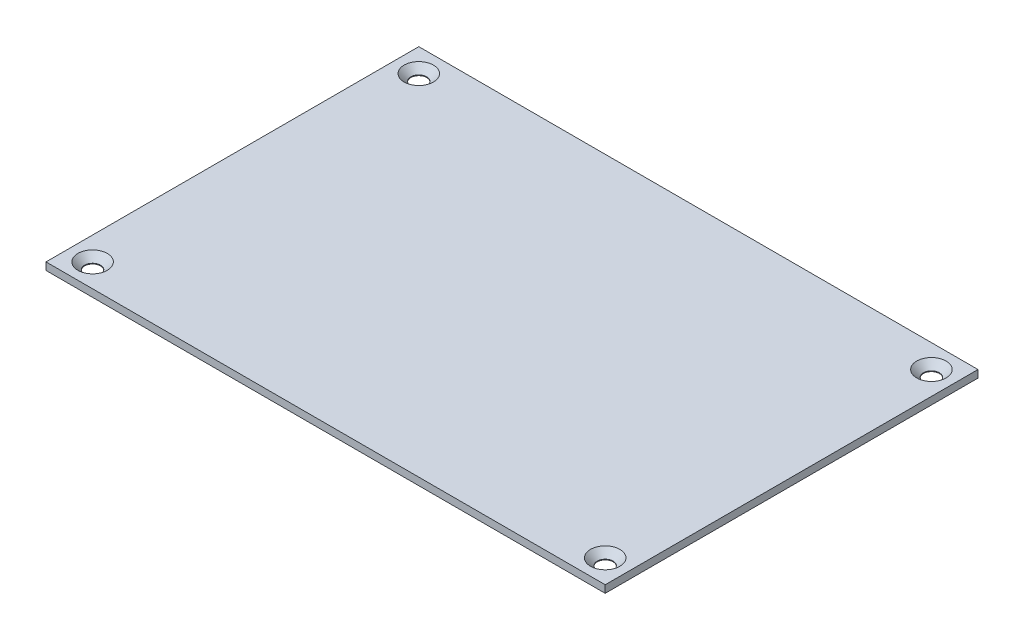
SolidWorks part; units mm, degrees
ref_plane "Front Plane" through (0, 0, 0) normal (0, 0, 1) x (1, 0, 0)
ref_plane "Top Plane" through (0, 0, 0) normal (0, 1, 0) x (1, 0, 0)
ref_plane "Right Plane" through (0, 0, 0) normal (1, 0, 0) x (0, 0, -1)
sketch "Sketch1" plane through (0, 0, 0) normal (0, 1, 0) x (1, 0, 0)
  line L1 (0, 0) -> (120, 0)
  line L2 (0, 0) -> (0, 80)
  line L3 (0, 80) -> (120, 80)
  line L4 (120, 0) -> (120, 80)
  dimension "D1" = 120
  dimension "D2" = 80
extrude "Boss-Extrude1" add sketch "Sketch1" along normal blind 1.6
sketch "Sketch2" plane through (0, 1.6, 0) normal (0, 1, 0) x (1, 0, 0)
  line L8 (5, 75) -> (5, 5)
  line L9 (5, 5) -> (115, 5)
  line L10 (115, 5) -> (115, 75)
  line L11 (115, 75) -> (5, 75)
  line L12 (5, 75) -> (5, 5)
  line L13 (5, 5) -> (115, 5)
  line L14 (115, 5) -> (115, 75)
  line L15 (115, 75) -> (5, 75)
  point P6 (5, 75)
  point P8 (5, 5)
  point P10 (115, 5)
  point P11 (115, 75)
  dimension "D1" = 5
hole_wizard "CSK for M3 Countersunk Flat Head Screw1" positions "Sketch2" profile "Sketch3" countersink size "M3" standard "ISO"
sketch "Sketch3" plane through (5, 1.6, -75) normal (1, 0, 0) x (0, 0, 1)
  line L0 (0, 0) -> (0, 31.0215)
  line L1 (0, 31.0215) -> (1.7, 30)
  line L2 (1.7, 30) -> (1.7, 1.45)
  line L3 (1.7, 1.45) -> (3.15, 0)
  line L5 (3.15, 0) -> (0, 0)
  line L6 (-1.7, 1.45) -> (-3.15, 0) construction
  line L10 (0, 31.0215) -> (-1.7, 30) construction
  line L11 (0, -6.35) -> (0, 107.95) construction
  dimension "Hole Dia." = 3.4
  dimension "Hole Depth" = 30
  dimension "Near C'Sink Dia." = 6.3
  dimension "Near C'Sink Angle" = 90
  dimension "Drill Angle" = 118
